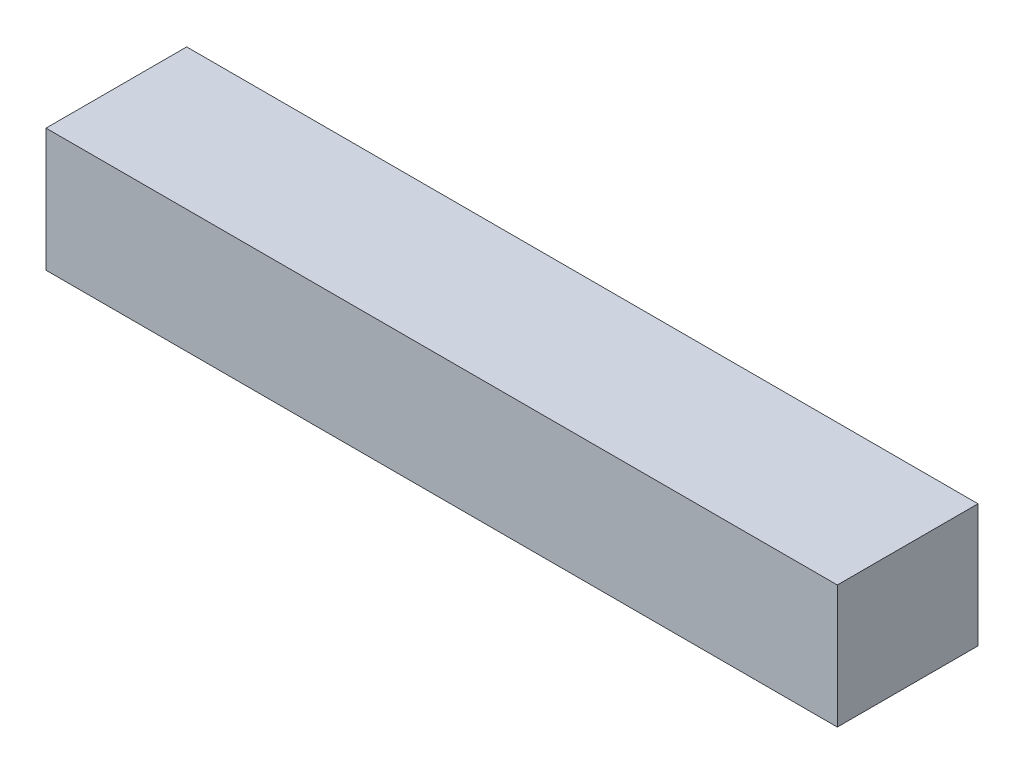
SolidWorks part; units mm, degrees
ref_plane "Front Plane" through (0, 0, 0) normal (0, 0, 1) x (1, 0, 0)
ref_plane "Top Plane" through (0, 0, 0) normal (0, 1, 0) x (1, 0, 0)
ref_plane "Right Plane" through (0, 0, 0) normal (1, 0, 0) x (0, 0, -1)
sketch "Sketch1" plane through (0, 0, 0) normal (1, 0, 0) x (0, 0, -1)
  line L1 (0, 0) -> (8, 0)
  line L2 (0, 0) -> (0, 7)
  line L3 (0, 7) -> (8, 7)
  line L4 (8, 0) -> (8, 7)
  dimension "D1" = 8
  dimension "D2" = 7
extrude "Boss-Extrude1" add sketch "Sketch1" along normal blind 45 contours L2 L3 L4 L1
